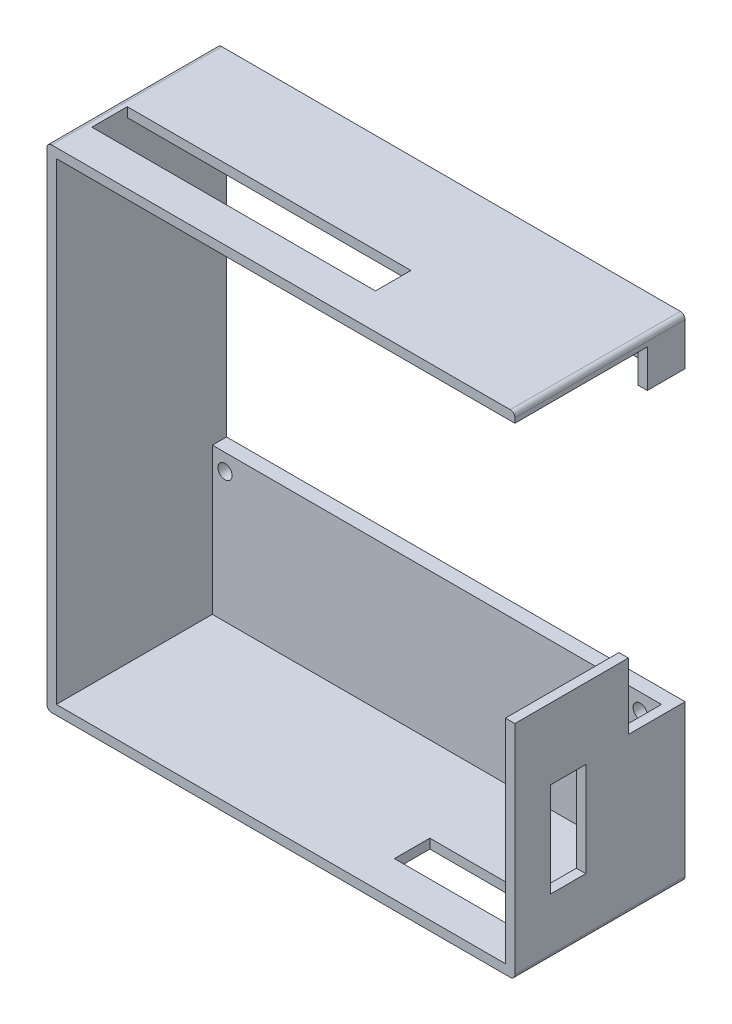
SolidWorks part; units mm, degrees
ref_plane "前视基准面" through (0, 0, 0) normal (0, 0, 1) x (1, 0, 0)
ref_plane "上视基准面" through (0, 0, 0) normal (0, 1, 0) x (1, 0, 0)
ref_plane "右视基准面" through (0, 0, 0) normal (1, 0, 0) x (0, 0, -1)
sketch "草图1" plane through (0, 0, 0) normal (0, 0, 1) x (1, 0, 0)
  line L1 (-47.5, -30.5) -> (47.5, -30.5)
  line L2 (-47.5, -30.5) -> (-47.5, 30.5)
  line L3 (-47.5, 30.5) -> (47.5, 30.5)
  line L4 (47.5, -30.5) -> (47.5, 30.5)
  line L5 (-47.5, -30.5) -> (47.5, 30.5) construction
  line L6 (-47.5, 30.5) -> (47.5, -30.5) construction
  line L10 (-49.5, 40.5) -> (49.5, 40.5)
  line L11 (49.5, 40.5) -> (49.5, -63.5)
  line L12 (49.5, -63.5) -> (-49.5, -63.5)
  line L13 (-49.5, -63.5) -> (-49.5, 40.5)
  circle A0 centre (43, 34) radius 1.5
  circle A1 centre (-44.8138, 34) radius 1.5
  circle A2 centre (-44.8138, -34) radius 1.5
  circle A3 centre (43, -34) radius 1.5
  point P0 (0, 0)
extrude "凸台-拉伸3" add sketch "草图1" along normal blind 3
sketch "草图3" plane through (0, 0, 3) normal (0, 0, 1) x (1, 0, 0)
  line L0 (-47.5, 38.5) -> (-47.5, -61.5)
  line L1 (-47.5, -61.5) -> (47.5, -61.5)
  line L2 (47.5, -61.5) -> (47.5, 38.5)
  line L3 (47.5, 38.5) -> (-47.5, 38.5)
  line L4 (-49.5, 40.5) -> (-49.5, -63.5)
  line L5 (-49.5, -63.5) -> (49.5, -63.5)
  line L6 (49.5, -63.5) -> (49.5, 40.5)
  line L7 (49.5, 40.5) -> (-49.5, 40.5)
  line L8 (-49.5, 40.5) -> (-49.5, -63.5)
  line L9 (-49.5, -63.5) -> (49.5, -63.5)
  line L10 (49.5, -63.5) -> (49.5, 40.5)
  line L11 (49.5, 40.5) -> (-49.5, 40.5)
  dimension "D1" = 0
  dimension "D2" = 2
extrude "凸台-拉伸4" add sketch "草图3" along normal blind 33
sketch "草图4" plane through (47.5, 0, 0) normal (-1, 0, 0) x (0, 0, 1)
  line L1 (3, 30.5) -> (12, 30.5)
  line L2 (12, 30.5) -> (12, -30.5)
  line L3 (12, -30.5) -> (3, -30.5)
  line L4 (3, 30.5) -> (0, 30.5)
  line L5 (0, 30.5) -> (0, -30.5)
  line L6 (0, -30.5) -> (3, -30.5)
extrude "切除-拉伸2" cut sketch "草图4" against normal blind 30
sketch "草图5" plane through (0, 40.5, 0) normal (0, 1, 0) x (1, 0, 0)
  line L0 (12.5, -28.5) -> (-47.5, -28.5)
  line L2 (-47.5, -21) -> (12.5, -21)
  line L4 (12.5, -21) -> (12.5, -28.5)
  line L7 (-47.5, -21) -> (-47.5, -28.5)
extrude "切除-拉伸3" cut sketch "草图5" against normal blind 30
sketch "草图6" plane through (47.5, 0, 0) normal (-1, 0, 0) x (0, 0, 1)
  line L0 (36, 38.5) -> (36, -16.5)
  line L1 (36, -61.5) -> (36, 38.5) construction
  line L2 (36, 38.5) -> (3, 38.5) construction
  line L3 (36, -16.5) -> (8, -16.5)
  line L4 (8, -16.5) -> (8, 38.5)
  line L5 (8, 38.5) -> (36, 38.5)
extrude "切除-拉伸4" cut sketch "草图6" against normal blind 30
sketch "草图7" plane through (47.5, 0, 0) normal (-1, 0, 0) x (0, 0, 1)
  line L3 (28.5, -31.5) -> (21, -31.5)
  line L4 (21, -31.5) -> (21, -51.5)
  line L5 (21, -51.5) -> (28.5, -51.5)
  line L6 (28.5, -51.5) -> (28.5, -31.5)
extrude "切除-拉伸5" cut sketch "草图7" against normal blind 30
sketch "草图8" plane through (0, -61.5, 0) normal (0, 1, 0) x (1, 0, 0)
  line L2 (40, -28.5) -> (16.5, -28.5)
  line L3 (16.5, -28.5) -> (16.5, -21)
  line L4 (16.5, -21) -> (40, -21)
  line L5 (40, -21) -> (40, -28.5)
extrude "切除-拉伸6" cut sketch "草图8" against normal blind 30
fillet "圆角1" radius 1 4 edges at (-49.5, 40.5, 18) (49.5, 40.5, 18) (49.5, -63.5, 18) (-49.5, -63.5, 18)
